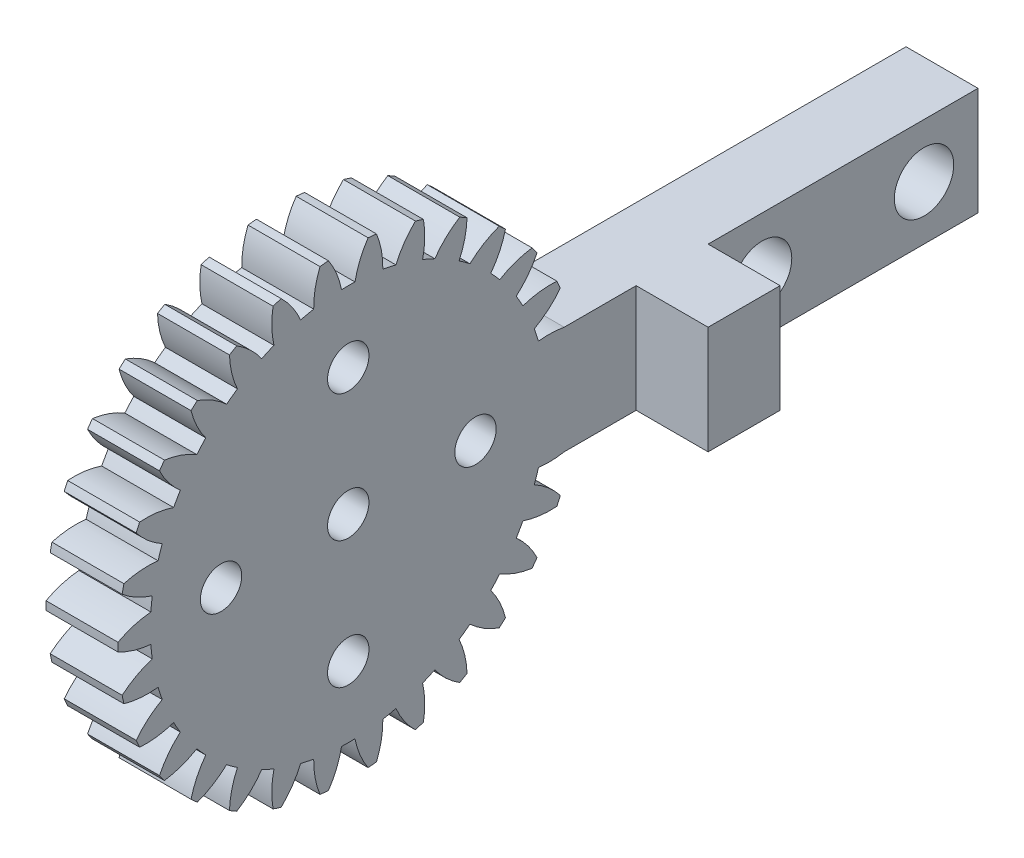
SolidWorks part; units mm, degrees
ref_plane "Plane1" through (0, 0, 0) normal (0, 0, 1) x (1, 0, 0)
ref_plane "Plane2" through (0, 0, 0) normal (0, 1, 0) x (1, 0, 0)
ref_plane "Plane3" through (0, 0, 0) normal (1, 0, 0) x (0, 0, -1)
other "Configuration Table"
sketch "HoldingSke" plane through (0, 0, 0) normal (0, 1, 0) x (1, 0, 0)
  line L0 (0, 0) -> (1.0825, -0.625)
  line L1 (-15, 0) -> (100, 0) construction
  line L2 (0, 0) -> (-2.1039, 2.3779)
  line L3 (0, 0) -> (-11.863, 4.5341)
  line L4 (0, 0) -> (7.479, 4.318)
  line L5 (0, 0) -> (-46.8476, -17.4728)
  line L6 (0, 0) -> (-3.3159, -2.2372)
  line L7 (-2.1039, 2.3779) -> (8.6586, 51.2059)
  line L8 (-76.2, 54.61) -> (-74.4, 54.61)
  line L9 (-71.009, 38.7566) -> (-53.1078, 45.2721)
  line L10 (-76.2, 71.12) -> (104.1128, 71.12)
  line L11 (0, 0) -> (-4, 0)
  line L12 (-76.2, 101.6) -> (-76.17, 101.6)
  line L13 (24.9733, 27.94) -> (52.9518, 28.4284)
  line L14 (24.9733, 27.94) -> (24.9743, 27.94)
  line L15 (24.9733, 27.94) -> (100.4006, 29.5858)
  line L16 (-63.627, -0.8) -> (-12.827, -0.8)
  circle A0 centre (0, 0) radius 5
  circle A1 centre (0, 0) radius 10.999
  circle A2 centre (0, 0) radius 37.5
  circle A3 centre (0, 0) radius 5
  dimension "MHD" = 21.998
  dimension "Hub_dia" = 75
  dimension "Bore" = 10
  dimension "MBD" = 10
  dimension "Num_teeth" = 30
  dimension "Pitch" = 1.25
  dimension "Overall_len" = 50
  dimension "Show_teeth" = 30
  dimension "Thickness" = 4
  dimension "OAL" = 50.0001
  dimension "T_dim" = 1.8
  dimension "Ap" = 20
  dimension "H" = 19.05
  dimension "Pitch_radius" = 180.3128
  dimension "Width" = 4
  dimension "Backlash" = 0.03
  dimension "Addendum_fac" = 1
  dimension "Dedendum_fac" = 1.25
  dimension "Clearance_fac" = 0.25
  dimension "Dedendum_add" = 0.001
  dimension "Module" = 0.8
sketch "BasProSke" plane through (0, 0, 0) normal (0, 1, 0) x (1, 0, 0)
  line L0 (-10, 0) -> (60, 0) construction
  line L1 (0, 0) -> (0, 12.8)
  line L2 (0, 0) -> (4, 0)
  line L3 (4, 0) -> (4, 12.8)
  line L4 (4, 12.8) -> (0, 12.8)
  dimension "Thickness" = 4
  dimension "Diameter" = 25.6
revolve "Base-Revolve" add sketch "BasProSke" angle 360 about L0
sketch "TooCutSke" plane through (0, 0, 0) normal (1, 0, 0) x (0, 0, -1)
  line L1 (0, 0) -> (0, 107) construction
  line L2 (0, 0) -> (-0.6805, 11.9807) construction
  line L3 (0, 0) -> (-2.5058, 23.8411) construction
  line L4 (-0.6805, 11.9807) -> (-1.2529, 11.9205) construction
  arc A0 (0.3724, 10.9927) -> (-0.3724, 10.9927) centre (0, 0) ccw
  arc A1 (1.1205, 12.7764) -> (-1.1205, 12.7764) centre (0, 0) ccw
  circle A2 centre (0, 0) radius 12 construction
  circle A3 centre (0, 0) radius 11.2763 construction
  arc A4 (-0.3724, 10.9927) -> (-1.1205, 12.7764) centre (-5.0822, 10.0661) ccw
  arc A5 (1.1205, 12.7764) -> (0.3724, 10.9927) centre (5.0822, 10.0661) ccw
  dimension "Root_dia" = 21.998
  dimension "Overcut_dia" = 25.6508
  dimension "Pitch_dia" = 24
  dimension "Base_dia" = 22.5526
  dimension "Flank_rad" = 4.8
  dimension "Half_ang" = 6
  dimension "Half_CT" = 0.5755
extrude "ToothCut" cut sketch "TooCutSke" along normal through all
fillet "Breaks" [suppressed] radius 0.016
fillet "RootFillets" [suppressed] radius 0.201
pattern_circular "TeethCuts" count 30 every 12 about axis through (-10, 0, 0) along (1, 0, 0) of "ToothCut", "RootFillets", "Breaks"
sketch "HubNeaOneSke" plane through (0, 0, 0) normal (-1, 0, 0) x (0, 0, 1)
  circle A0 centre (0, 0) radius 10.999
  dimension "Diameter" = 21.998
extrude "HubNearOne" [suppressed] add sketch "HubNeaOneSke" along normal blind 46.0001
sketch "HubNeaBotSke" plane through (0, 0, 0) normal (-1, 0, 0) x (0, 0, 1)
  circle A0 centre (0, 0) radius 10.999
  dimension "Diameter" = 21.998
extrude "HubNearBoth" [suppressed] add sketch "HubNeaBotSke" along normal blind 23
ref_plane "FarPln" through (4, 0, 0) normal (1, 0, 0) x (0, 0, -1)
sketch "HubFarSke" plane through (4, 0, 0) normal (1, 0, 0) x (0, 0, -1)
  circle A0 centre (0, 0) radius 10.999
  dimension "Diameter" = 21.998
extrude "HubFar" [suppressed] add sketch "HubFarSke" along normal blind 23
sketch "BorSke" plane through (0, 0, 0) normal (1, 0, 0) x (0, 0, -1)
  circle A0 centre (0, 0) radius 5
  dimension "Diameter" = 10
extrude "Bore" cut sketch "BorSke" along normal mid plane 100.0001
sketch "KeySke" plane through (0, 0, 0) normal (1, 0, 0) x (0, 0, -1)
  line L0 (-2, 0) -> (-2, 6.8)
  line L1 (-2, 6.8) -> (2, 6.8)
  line L2 (2, 6.8) -> (2, 0)
  line L3 (0, 0) -> (0, 34) construction
  line L4 (-2, 0) -> (2, 0)
  dimension "Width" = 4
  dimension "Offset" = 6.8
extrude "Keyway" [suppressed] cut sketch "KeySke" along normal mid plane 100.0001
pattern_circular "Keyway2" [suppressed] count 2 every 90 about axis through (-10, 0, 0) along (1, 0, 0)
sketch "草图1" plane through (4, 0, 0) normal (1, 0, 0) x (0, 0, -1)
  line L0 (-14.8718, 0) -> (26.5062, 0) construction
  line L1 (0, 17.4416) -> (0, -24.7441) construction
  line L3 (9.5432, -3) -> (35, -3)
  line L4 (9.5432, -3) -> (9.5432, 3)
  line L5 (9.5432, 3) -> (35, 3)
  line L6 (35, -3) -> (35, 3)
  point P9 (9.5432, 0)
  dimension "D1" = 6
  dimension "D2" = 35
extrude "凸台-拉伸1" add sketch "草图1" against normal blind 4
sketch "草图2" plane through (0, 3, 0) normal (0, 1, 0) x (1, 0, 0)
  line L1 (4, 35) -> (2, 35)
  line L2 (4, 35) -> (4, 20)
  line L3 (4, 20) -> (2, 20)
  line L4 (2, 35) -> (2, 20)
  dimension "D1" = 2
  dimension "D2" = 15
extrude "切除-拉伸1" cut sketch "草图2" against normal up to next
sketch "草图3" plane through (2, 0, 0) normal (1, 0, 0) x (0, 0, -1)
  line L0 (20, -3) -> (20, 3) construction
  line L1 (35, -3) -> (35, 3) construction
  circle A0 centre (23, 0) radius 1.65
  circle A1 centre (32, 0) radius 1.65
  point P8 (35, 0)
  dimension "D1" = 3.3
  dimension "D2" = 3.3
  dimension "D3" = 3
  dimension "D4" = 3
extrude "切除-拉伸2" cut sketch "草图3" against normal up to next
sketch "草图4" plane through (0, 0, 0) normal (-1, 0, 0) x (0, 0, 1)
  circle A0 centre (0, 0) radius 5
extrude "凸台-拉伸2" add sketch "草图4" against normal blind 4
sketch "草图5" plane through (0, 0, 0) normal (-1, 0, 0) x (0, 0, 1)
  circle A0 centre (0, 0) radius 12
  dimension "D1" = 24
sketch "草图6" plane through (0, 0, 0) normal (-1, 0, 0) x (0, 0, 1)
  circle A0 centre (0, 0) radius 7.0711 construction
  circle A1 centre (-7.0711, 0) radius 1.15
  circle A2 centre (0, 7.0711) radius 1.15
  circle A3 centre (7.0711, 0) radius 1.15
  circle A4 centre (0, -7.0711) radius 1.15
  circle A5 centre (0, 0) radius 1.15
  dimension "D1" = 2.3
  dimension "D2" = 2.3
extrude "切除-拉伸3" cut sketch "草图6" against normal up to next
sketch "草图7" plane through (2, 0, 0) normal (1, 0, 0) x (0, 0, -1)
  line L1 (20, 3) -> (35, 3)
  line L2 (20, 3) -> (20, -3)
  line L3 (20, -3) -> (35, -3)
  line L4 (35, 3) -> (35, -3)
  circle A0 centre (23, 0) radius 1.65
  circle A2 centre (32, 0) radius 1.65
extrude "凸台-拉伸3" add sketch "草图7" along normal blind 2
sketch "草图8" plane through (0, -3, 0) normal (0, -1, 0) x (1, 0, 0)
  line L0 (4, -12.0012) -> (4, -35) construction
  line L1 (4, -20) -> (8, -20)
  line L2 (4, -20) -> (4, -16)
  line L3 (4, -16) -> (8, -16)
  line L4 (8, -20) -> (8, -16)
  line L5 (4, -20) -> (8, -20) construction
  dimension "D1" = 4
extrude "凸台-拉伸4" add sketch "草图8" against normal blind 6
equation "' \"Module@HoldingSke\" = 6.35"
equation "' \"Num_teeth@HoldingSke\" = 12"
equation "' \"Ap@HoldingSke\" =  20"
equation "' \"Ap@HoldingSke\" = 20"
equation "' \"Width@HoldingSke\" = 0.5 * 25.4"
equation "' \"Hub_dia@HoldingSke\"= 1 * 25.4"
equation "' \"Hub_dia@HoldingSke\" = 1 * 25.4"
equation "' \"Overall_len@HoldingSke\" = 1.0 * 25.4"
equation "' \"Bore@HoldingSke\" = 0.75 * 25.4"
equation "' \"T_dim@HoldingSke\" = 0.1 * 25.4"
equation "' \"Width@KeySke\" = 0.25 * 25.4"
equation "' \"Show_teeth@HoldingSke\" = 13"
equation "' \"Backlash@HoldingSke\" = 0.009 * 25.4"
equation "' \"Addendum_fac@HoldingSke\" = 1.0"
equation "' \"Dedendum_fac@HoldingSke\" = 1.25"
equation "' \"Dedendum_add@HoldingSke\" = 0.00005 * 25.4"
equation "' \"Clearance_fac@HoldingSke\" = 0.25"
equation "\"Pitch@HoldingSke\" = 1 / \"Module@HoldingSke\""
equation "\"Overcut_dia@TooCutSke\" = (\"Num_teeth@HoldingSke\" + 2 * \"Addendum_fac@HoldingSke\") / \"Pitch@HoldingSke\" + 0.002 * 25.4"
equation "\"Pitch_dia@TooCutSke\" = \"Num_teeth@HoldingSke\" / \"Pitch@HoldingSke\""
equation "\"Base_dia@TooCutSke\" = \"Num_teeth@HoldingSke\" / \"Pitch@HoldingSke\" * cos((\"Ap@HoldingSke\"  * 3.14159265 / 180))"
equation "\"Root_dia@TooCutSke\" = (\"Num_teeth@HoldingSke\" + 2) / \"Pitch@HoldingSke\" - 2 * (\"Addendum_fac@HoldingSke\" + \"Dedendum_fac@HoldingSke\") / \"Pitch@HoldingSke\" - \"Dedendum_add@HoldingSke\" * 2"
equation "\"Half_ang@TooCutSke\" = 180 / \"Num_teeth@HoldingSke\""
equation "\"Half_CT@TooCutSke\" = \"Num_teeth@HoldingSke\" / \"Pitch@HoldingSke\" * sin((3.14159265 / 2 / \"Num_teeth@HoldingSke\")) / 2 - 7 * \"Backlash@HoldingSke\" / 4"
equation "\"Flank_rad@TooCutSke\" = \"Num_teeth@HoldingSke\" / \"Pitch@HoldingSke\" / 5"
equation "\"Radius@RootFillets\" = \"Clearance_fac@HoldingSke\" / \"Pitch@HoldingSke\" + \"Dedendum_add@HoldingSke\""
equation "\"Break_rad@Breaks\" = 0.02 / \"Pitch@HoldingSke\""
equation "\"Thickness@HoldingSke\" = \"Width@HoldingSke\""
equation "\"OAL@HoldingSke\" = \"Thickness@HoldingSke\""
equation "\"MHD@HoldingSke\" = (\"Num_teeth@HoldingSke\" + 2) / \"Pitch@HoldingSke\" - 2 * (\"Addendum_fac@HoldingSke\" + \"Dedendum_fac@HoldingSke\")  / \"Pitch@HoldingSke\" - \"Dedendum_add@HoldingSke\" * 2"
equation "\"MBD@HoldingSke\" = (\"Num_teeth@HoldingSke\" + 2) / \"Pitch@HoldingSke\" - 2 * (\"Addendum_fac@HoldingSke\" + \"Dedendum_fac@HoldingSke\")  / \"Pitch@HoldingSke\" - \"Dedendum_add@HoldingSke\" * 2 - 0.002 * 25.4"
equation "\"MHD@HoldingSke\" = ((sgn( \"MHD@HoldingSke\" - \"Hub_dia@HoldingSke\" )-1)*( \"MHD@HoldingSke\" - \"Hub_dia@HoldingSke\" ))/-2+ \"Hub_dia@HoldingSke\""
equation "\"MBD@HoldingSke\" = ((sgn( \"MBD@HoldingSke\" - \"Bore@HoldingSke\" )-1)*( \"MBD@HoldingSke\" - \"Bore@HoldingSke\" ))/-2+ \"Bore@HoldingSke\""
equation "\"OAL@HoldingSke\" = ((sgn( \"OAL@HoldingSke\" - \"Overall_len@HoldingSke\" )+1)*( \"OAL@HoldingSke\" - \"Overall_len@HoldingSke\" ))/2 + \"Overall_len@HoldingSke\" + 0.000002 * 25.4"
equation "\"Num_teeth@TeethCuts\" = int( \"Show_teeth@HoldingSke\" ) + 1"
equation "\"Num_teeth@TeethCuts\" = ((sgn( \"Num_teeth@TeethCuts\" - \"Num_teeth@HoldingSke\" )-1)*( \"Num_teeth@TeethCuts\" - \"Num_teeth@HoldingSke\" ))/-2+ \"Num_teeth@HoldingSke\""
equation "\"Num_teeth@TeethCuts\" = ((sgn( \"Num_teeth@TeethCuts\" - 2.0)+1)*( \"Num_teeth@TeethCuts\" - 2.0))/2 +2.0"
equation "\"Angle@TeethCuts\" = 360.0 / \"Num_teeth@HoldingSke\""
equation "\"Diameter@BasProSke\" = (\"Num_teeth@HoldingSke\" + 2 * \"Addendum_fac@HoldingSke\") / \"Pitch@HoldingSke\""
equation "\"Thickness@BasProSke\"  = \"Thickness@HoldingSke\""
equation "' \"Fillet_rad@BasProSke\" =  \"Thickness@HoldingSke\" * 0.05"
equation "' \"Fillet_rad@BasProSke\" = \"Thickness@HoldingSke\" * 0.05"
equation "\"MHD@HoldingSke\" = ((sgn( \"MHD@HoldingSke\" - \"Root_dia@TooCutSke\" )-1)*( \"MHD@HoldingSke\" - \"Root_dia@TooCutSke\" ))/-2+ \"Root_dia@TooCutSke\""
equation "\"Diameter@HubNeaOneSke\" = \"MHD@HoldingSke\""
equation "\"Length@HubNearOne\" = \"OAL@HoldingSke\" - \"Thickness@BasProSke\""
equation "\"Diameter@HubNeaBotSke\" = \"MHD@HoldingSke\""
equation "\"Length@HubNearBoth\" = ( \"OAL@HoldingSke\" - \"Thickness@BasProSke\" ) / 2.0"
equation "\"Thickness@FarPln\" = \"Thickness@BasProSke\""
equation "\"Diameter@HubFarSke\" = \"MHD@HoldingSke\""
equation "\"Length@HubFar\" = ( \"OAL@HoldingSke\" - \"Thickness@BasProSke\" ) / 2.0"
equation "\"Diameter@BorSke\" = \"MBD@HoldingSke\""
equation "\"D1@Bore\" = \"OAL@HoldingSke\" * 2.0"
equation "\"D1@Keyway\" = \"OAL@HoldingSke\" * 2.0"
equation "\"Offset@KeySke\" = \"T_dim@HoldingSke\" + \"MBD@HoldingSke\" / 2.0"
